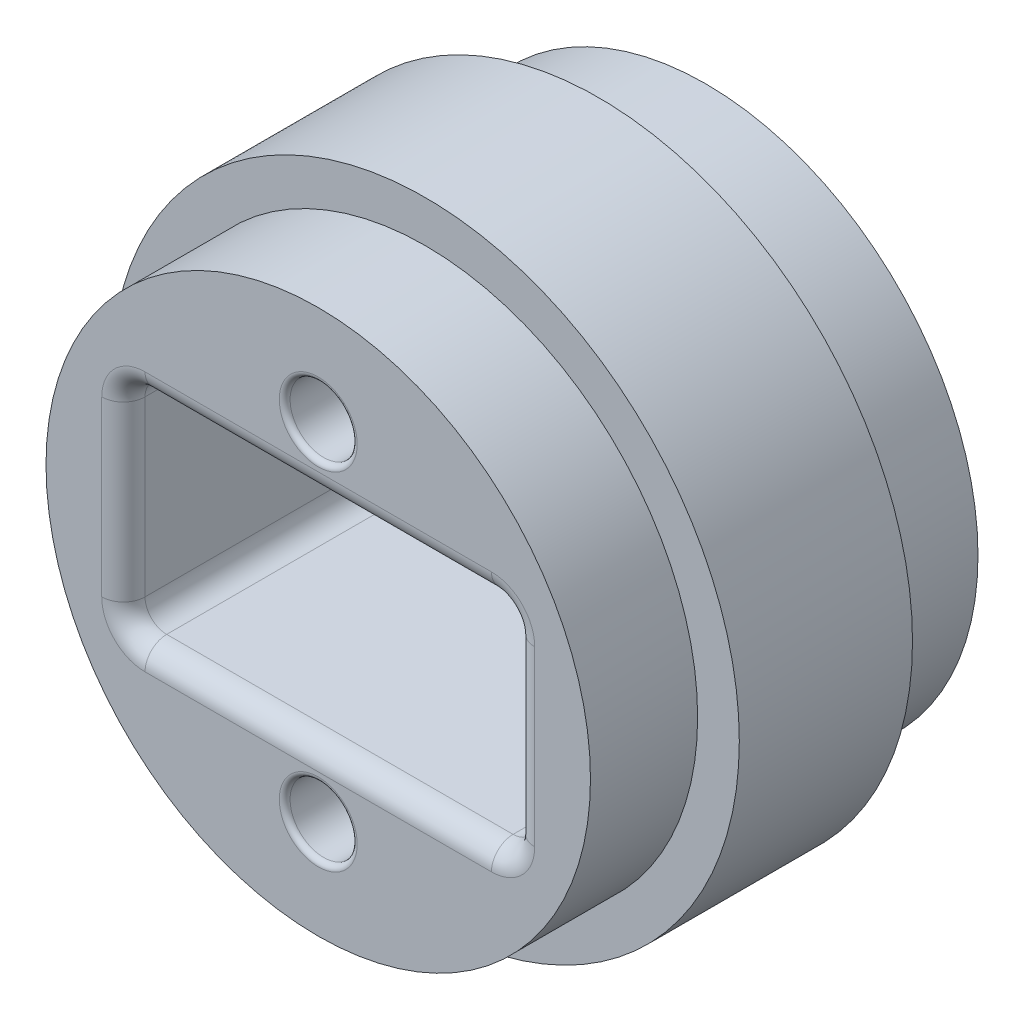
SolidWorks part; units mm, degrees
ref_plane "Plan de face" through (0, 0, 0) normal (0, 0, 1) x (1, 0, 0)
ref_plane "Plan de dessus" through (0, 0, 0) normal (0, 1, 0) x (1, 0, 0)
ref_plane "Plan de droite" through (0, 0, 0) normal (1, 0, 0) x (0, 0, -1)
sketch "Esquisse1" plane through (0, 0, 0) normal (0, 0, 1) x (1, 0, 0)
  circle A0 centre (0, 0) radius 14.5
  dimension "D1" = 29
extrude "Boss.-Extru.1" add sketch "Esquisse1" along normal blind 8
sketch "Esquisse2" plane through (0, 0, 8) normal (0, 0, 1) x (1, 0, 0)
  circle A0 centre (0, 0) radius 12.575
  dimension "D1" = 25.15
extrude "Boss.-Extru.2" add sketch "Esquisse2" along normal blind 4.95 and the other way blind 12.95
sketch "Esquisse3" plane through (0, 0, 12.95) normal (0, 0, 1) x (1, 0, 0)
  line L0 (0, 0) -> (-4.1546, 0) construction
  line L1 (-8, -5) -> (8, -5)
  line L2 (-9, -4) -> (-9, 4)
  line L3 (-8, 5) -> (8, 5)
  line L4 (9, -4) -> (9, 4)
  line L5 (-9, -5) -> (9, 5) construction
  line L6 (-9, 5) -> (9, -5) construction
  arc A0 (8, 5) -> (9, 4) centre (8, 4) cw
  arc A1 (9, -4) -> (8, -5) centre (8, -4) cw
  arc A2 (-8, -5) -> (-9, -4) centre (-8, -4) cw
  arc A3 (-9, 4) -> (-8, 5) centre (-8, 4) cw
  circle A4 centre (0, 8) radius 1.55
  circle A5 centre (0, -8) radius 1.55
  point P0 (0, 0)
  dimension "D3" = 1
  dimension "D4" = 3.1
  dimension "D1" = 18
  dimension "D2" = 10
  dimension "D5" = 3
extrude "Enlèv. mat.-Extru.1" cut sketch "Esquisse3" against normal through all
fillet "Congé1" radius 1 16 edges at (8.7071, 4.7071, 12.95) (9, 0, 12.95) (8.7071, -4.7071, 12.95) (0, -5, 12.95) (-8.7071, -4.7071, 12.95) (-9, 0, 12.95) (-8.7071, 4.7071, 12.95) (0, 5, 12.95) (8.7071, 4.7071, -4.95) (9, 0, -4.95) (8.7071, -4.7071, -4.95) (0, -5, -4.95) (-8.7071, -4.7071, -4.95) (-9, 0, -4.95) (-8.7071, 4.7071, -4.95) (0, 5, -4.95)
fillet "Congé2" radius 0.25 4 edges at (1.55, 8, 12.95) (-1.55, -8, 12.95) (-1.55, -8, -4.95) (1.55, 8, -4.95)
